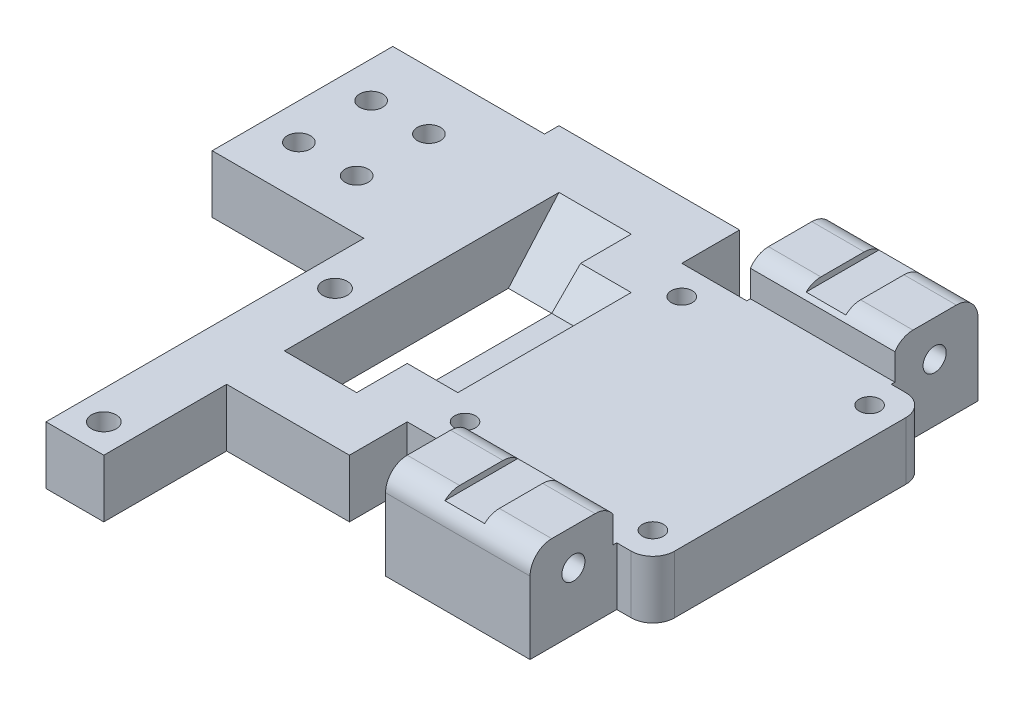
SolidWorks part; units mm, degrees
ref_plane "Front" through (0, 0, 0) normal (0, 0, 1) x (1, 0, 0)
ref_plane "Top" through (0, 0, 0) normal (0, 1, 0) x (1, 0, 0)
ref_plane "Right" through (0, 0, 0) normal (1, 0, 0) x (0, 0, -1)
sketch "Sketch1" plane through (0, 0, 0) normal (0, 1, 0) x (1, 0, 0)
  line L1 (0, 0) -> (300, 0)
  line L2 (0, 0) -> (0, -20)
  line L3 (0, -20) -> (300, -20)
  line L4 (300, 0) -> (300, -20)
  dimension "D1" = 20
  dimension "D2" = 300
extrude "Boss-Extrude1" add sketch "Sketch1" along normal blind 8
sketch "Sketch2" plane through (0, 0, 20) normal (0, 0, 1) x (1, 0, 0)
  line L0 (0, 8) -> (300, 8) construction
  line L1 (0, 0) -> (34, 0)
  line L2 (0, 0) -> (0, 8)
  line L3 (0, 8) -> (34, 8)
  line L4 (34, 0) -> (34, 8)
  line L5 (266, 8) -> (300, 8)
  line L6 (300, 0) -> (300, 8)
  line L7 (266, 0) -> (300, 0)
  line L8 (266, 0) -> (266, 8)
  dimension "D1" = 34
  dimension "D2" = 2
extrude "Boss-Extrude2" add sketch "Sketch2" along normal blind 9
sketch "Sketch3" plane through (0, 0, 0) normal (0, 0, -1) x (-1, 0, 0)
  line L0 (-300, 8) -> (0, 8) construction
  line L1 (0, 0) -> (-34, 0)
  line L2 (0, 0) -> (0, 8)
  line L3 (0, 8) -> (-34, 8)
  line L4 (-34, 0) -> (-34, 8)
  line L5 (-300, 0) -> (-300, 8)
  line L6 (-266, 8) -> (-300, 8)
  line L7 (-266, 0) -> (-266, 8)
  line L8 (-266, 0) -> (-300, 0)
  dimension "D1" = 34
  dimension "D2" = 2
extrude "Boss-Extrude3" add sketch "Sketch3" along normal blind 9
sketch "Sketch4" plane through (0, 8, 0) normal (0, 1, 0) x (1, 0, 0)
  line L0 (0, 9) -> (34, 9) construction
  line L1 (0, 9) -> (0, -29) construction
  circle A0 centre (4, 5) radius 1.45
  circle A1 centre (30, 5) radius 1.45
  circle A2 centre (30, -25) radius 1.45
  circle A3 centre (4, -25) radius 1.45
  circle A4 centre (296, -25) radius 1.45
  circle A5 centre (296, 5) radius 1.45
  circle A6 centre (270, -25) radius 1.45
  circle A7 centre (270, 5) radius 1.45
  dimension "D1" = 2.9
  dimension "D2" = 4
  dimension "D3" = 4
  dimension "D4" = 2
  dimension "D5" = 2
  dimension "D6" = 2
extrude "Cut-Extrude1" cut sketch "Sketch4" against normal through all
sketch "Sketch5" plane through (0, 0, 20) normal (0, 0, 1) x (1, 0, 0)
  line L0 (34, 8) -> (266, 8) construction
  line L1 (266, 0) -> (241, 0)
  line L2 (266, 0) -> (266, 8)
  line L3 (266, 8) -> (241, 8)
  line L4 (241, 0) -> (241, 8)
  dimension "D1" = 25
extrude "Boss-Extrude4" add sketch "Sketch5" along normal blind 17
sketch "Sketch6" plane through (0, 0, 0) normal (0, 0, -1) x (-1, 0, 0)
  line L0 (-266, 0) -> (-34, 0) construction
  line L1 (-266, 8) -> (-241, 8)
  line L2 (-266, 8) -> (-266, 0)
  line L3 (-266, 0) -> (-241, 0)
  line L4 (-241, 8) -> (-241, 0)
  dimension "D1" = 25
extrude "Boss-Extrude5" add sketch "Sketch6" along normal blind 17
sketch "Sketch7" plane through (0, 8, 0) normal (0, 1, 0) x (1, 0, 0)
  line L0 (266, -37) -> (241, -37) construction
  line L1 (259, -29) -> (249, -29)
  line L2 (259, -29) -> (259, 9)
  line L3 (259, 9) -> (249, 9)
  line L4 (249, -29) -> (249, 9)
  line L5 (241, -37) -> (241, -20) construction
  dimension "D1" = 10
  dimension "D2" = 38
  dimension "D3" = 8
  dimension "D4" = 8
extrude "Cut-Extrude2" cut sketch "Sketch7" against normal through all
sketch "Sketch8" plane through (0, 8, 0) normal (0, 1, 0) x (1, 0, 0)
  line L0 (259, -29) -> (259, 9) construction
  line L1 (259, -18) -> (266, -18)
  line L2 (259, -18) -> (259, -2)
  line L3 (259, -2) -> (266, -2)
  line L4 (266, -18) -> (266, -2)
  line L5 (266, -37) -> (241, -37) construction
  dimension "D1" = 7
  dimension "D2" = 16
  dimension "D3" = 19
extrude "Cut-Extrude3" cut sketch "Sketch8" against normal blind 4
sketch "Sketch9" plane through (259, 0, 0) normal (-1, 0, 0) x (0, 0, 1)
  line L0 (18, 4) -> (22, 8)
  line L1 (29, 8) -> (18, 8) construction
  line L2 (22, 8) -> (18, 8)
  line L3 (18, 8) -> (18, 4)
  line L4 (2, 4) -> (-2, 8)
  line L5 (2, 8) -> (-9, 8) construction
  line L6 (-2, 8) -> (2, 8)
  line L7 (2, 8) -> (2, 4)
  dimension "D1" = 4
  dimension "D2" = 4
extrude "Cut-Extrude4" cut sketch "Sketch9" against normal blind 7
sketch "Sketch10" plane through (259, 0, 0) normal (-1, 0, 0) x (0, 0, 1)
  line L0 (-9, 8) -> (-2, 0)
  line L1 (29, 0) -> (-9, 0) construction
  line L2 (-2, 0) -> (-9, 0)
  line L3 (-9, 0) -> (-9, 8)
  line L4 (29, 8) -> (22, 0)
  line L5 (22, 0) -> (29, 0)
  line L6 (29, 0) -> (29, 8)
  line L7 (-51.4523, 12.1971) -> (-51.8778, 12.5861)
  line M6 (-9, 8) -> (-9, 0)
  line M7 (-9, 0) -> (29, 0)
  line M8 (29, 0) -> (29, 8)
  dimension "D1" = 7
  dimension "D2" = 7
extrude "Boss-Extrude6" add sketch "Sketch10" along normal blind 10 contours L0 M6 M7 | L4 M8 M7
sketch "Sketch12" plane through (0, 0, 37) normal (0, 0, 1) x (1, 0, 0)
  line L0 (241, 0) -> (266, 0) construction
  line L1 (241, 8) -> (249, 8)
  line L2 (241, 8) -> (241, 0)
  line L3 (241, 0) -> (249, 0)
  line L4 (249, 8) -> (249, 0)
  dimension "D1" = 8
extrude "Boss-Extrude7" add sketch "Sketch12" along normal blind 17
sketch "Sketch13" plane through (0, 8, 0) normal (0, 1, 0) x (1, 0, 0)
  line L0 (249, -54) -> (241, -54) construction
  line L1 (249, -54) -> (249, -37) construction
  circle A0 centre (245, -50) radius 1.7
  circle A1 centre (245, -18) radius 1.7
  dimension "D1" = 3.4
  dimension "D2" = 4
  dimension "D3" = 4
  dimension "D4" = 2
extrude "Cut-Extrude6" cut sketch "Sketch13" against normal through all
sketch "Sketch14" plane through (0, 0, 29) normal (0, 0, 1) x (1, 0, 0)
  line L1 (295, 13) -> (275, 13)
  line L2 (295, 13) -> (295, 0)
  line L3 (295, 0) -> (275, 0)
  line L4 (275, 13) -> (275, 0)
  line L5 (266, 0) -> (300, 0) construction
  line L7 (266, 8) -> (266, 0) construction
  dimension "D1" = 20
  dimension "D2" = 9
  dimension "D3" = 13
extrude "Boss-Extrude8" add sketch "Sketch14" along normal blind 12
sketch "Sketch15" plane through (295, 0, 0) normal (1, 0, 0) x (0, 0, -1)
  line L0 (-41, 0) -> (-41, 13) construction
  line L1 (-41, 13) -> (-29, 13) construction
  circle A0 centre (-35, 8) radius 1.6
  dimension "D1" = 3.2
  dimension "D2" = 6
  dimension "D3" = 5
extrude "Cut-Extrude7" cut sketch "Sketch15" against normal blind 20
sketch "Sketch16" plane through (0, 0, -9) normal (0, 0, -1) x (-1, 0, 0)
  line L1 (-295, 13) -> (-275, 13)
  line L2 (-295, 13) -> (-295, 0)
  line L3 (-295, 0) -> (-275, 0)
  line L4 (-275, 13) -> (-275, 0)
  line L5 (-300, 0) -> (-266, 0) construction
  line L6 (-266, 0) -> (-266, 8) construction
  dimension "D1" = 20
  dimension "D2" = 9
  dimension "D3" = 13
extrude "Boss-Extrude9" add sketch "Sketch16" along normal blind 12
sketch "Sketch17" plane through (295, 0, 0) normal (1, 0, 0) x (0, 0, -1)
  line L1 (21, 13) -> (21, 0) construction
  line L2 (21, 13) -> (9, 13) construction
  circle A0 centre (15, 8) radius 1.6
  dimension "D1" = 3.2
  dimension "D2" = 5
  dimension "D3" = 6
extrude "Cut-Extrude8" cut sketch "Sketch17" against normal blind 20
sketch "Sketch18" plane through (0, 0, -9) normal (0, 0, -1) x (-1, 0, 0)
  line L1 (-25, 13) -> (-5, 13)
  line L2 (-25, 13) -> (-25, 0)
  line L3 (-25, 0) -> (-5, 0)
  line L4 (-5, 13) -> (-5, 0)
  line L5 (-34, 0) -> (0, 0) construction
  line L6 (-34, 8) -> (-34, 0) construction
  dimension "D1" = 20
  dimension "D2" = 9
  dimension "D3" = 13
extrude "Boss-Extrude10" add sketch "Sketch18" along normal blind 12
sketch "Sketch19" plane through (5, 0, 0) normal (-1, 0, 0) x (0, 0, 1)
  line L0 (-21, 0) -> (-21, 13) construction
  line L1 (-21, 13) -> (-9, 13) construction
  circle A0 centre (-15, 8) radius 1.6
  dimension "D1" = 3.2
  dimension "D2" = 6
  dimension "D3" = 5
extrude "Cut-Extrude9" cut sketch "Sketch19" against normal blind 20
sketch "Sketch20" plane through (0, 0, 29) normal (0, 0, 1) x (1, 0, 0)
  line L1 (5, 13) -> (25, 13)
  line L2 (5, 13) -> (5, 0)
  line L3 (5, 0) -> (25, 0)
  line L4 (25, 13) -> (25, 0)
  line L5 (0, 0) -> (34, 0) construction
  line L6 (34, 0) -> (34, 8) construction
  dimension "D1" = 20
  dimension "D2" = 9
  dimension "D3" = 13
extrude "Boss-Extrude11" add sketch "Sketch20" along normal blind 12
sketch "Sketch21" plane through (5, 0, 0) normal (-1, 0, 0) x (0, 0, 1)
  line L0 (41, 13) -> (41, 0) construction
  line L2 (41, 13) -> (29, 13) construction
  circle A0 centre (35, 8) radius 1.6
  dimension "D1" = 3.2
  dimension "D2" = 6
  dimension "D3" = 5
extrude "Cut-Extrude10" cut sketch "Sketch21" against normal blind 20
fillet "Fillet6" radius 3 8 edges at (15, 13, 41) (15, 13, 29) (15, 13, -9) (15, 13, -21) (285, 13, 41) (285, 13, 29) (285, 13, -9) (285, 13, -21)
sketch "Sketch28" plane through (0, 0, 0) normal (-1, 0, 0) x (0, 0, 1)
  line L1 (78.9453, 217.6934) -> (-119.9362, 217.6934)
  line L2 (78.9453, 217.6934) -> (78.9453, -338.6618)
  line L3 (78.9453, -338.6618) -> (-119.9362, -338.6618)
  line L4 (-119.9362, 217.6934) -> (-119.9362, -338.6618)
extrude "Cut-Extrude14" cut sketch "Sketch28" against normal blind 220
sketch "Sketch29" plane through (0, 0, 0) normal (0, 0, -1) x (-1, 0, 0)
  line L1 (-241, 0) -> (-220, 0)
  line L2 (-241, 0) -> (-241, 8)
  line L3 (-241, 8) -> (-220, 8)
  line L4 (-220, 0) -> (-220, 8)
extrude "Boss-Extrude12" add sketch "Sketch29" along normal blind 15
sketch "Sketch30" plane through (0, 0, 0) normal (0, -1, 0) x (-1, 0, 0)
  line L1 (-220, -20) -> (-241, -20)
  line L2 (-220, -20) -> (-220, -10)
  line L3 (-220, -10) -> (-241, -10)
  line L4 (-241, -20) -> (-241, -10)
  dimension "D1" = 21
  dimension "D2" = 10
extrude "Cut-Extrude15" cut sketch "Sketch30" against normal through all
sketch "Sketch31" plane through (0, 0, 0) normal (0, -1, 0) x (-1, 0, 0)
  line L0 (-220, -10) -> (-220, 15) construction
  line L1 (-241, 15) -> (-220, 15) construction
  line L2 (-220, -10) -> (-241, -10) construction
  circle A0 centre (-225, 7) radius 1.6
  circle A1 centre (-225, -3) radius 1.6
  circle A2 centre (-233, 7) radius 1.6
  circle A3 centre (-233, -3) radius 1.6
  dimension "D1" = 3.2
  dimension "D2" = 3.2
  dimension "D3" = 3.2
  dimension "D4" = 3.2
  dimension "D5" = 5
  dimension "D6" = 8
  dimension "D7" = 5
  dimension "D8" = 7
  dimension "D9" = 8
  dimension "D10" = 8
  dimension "D11" = 7
  dimension "D12" = 8
extrude "Cut-Extrude16" cut sketch "Sketch31" against normal through all
fillet "Fillet7" radius 3 2 edges at (300, 4, -9) (300, 4, 29)
sketch "Sketch32" plane through (0, 13, 0) normal (0, 1, 0) x (1, 0, 0)
  line L0 (295, -38) -> (295, -32) construction
  line L1 (287.75, -42.4531) -> (282.25, -42.4531)
  line L2 (287.75, -42.4531) -> (287.75, 28.0104)
  line L3 (287.75, 28.0104) -> (282.25, 28.0104)
  line L4 (282.25, -42.4531) -> (282.25, 28.0104)
  dimension "D1" = 5.5
  dimension "D2" = 7.25
extrude "Cut-Extrude17" cut sketch "Sketch32" against normal blind 0.8
sketch "Sketch33" plane through (0, 0, 29) normal (0, 0, -1) x (-1, 0, 0)
  line L1 (-275, 8) -> (-295, 8)
  line L2 (-275, 8) -> (-275, 12.9638)
  line L3 (-275, 12.9638) -> (-295, 12.9638)
  line L4 (-295, 8) -> (-295, 12.9638)
  dimension "D1" = 20
extrude "Cut-Extrude18" cut sketch "Sketch33" against normal blind 0.5
sketch "Sketch34" plane through (0, 0, -9) normal (0, 0, 1) x (1, 0, 0)
  line L1 (275, 8) -> (295, 8)
  line L2 (275, 8) -> (275, 19.9424)
  line L3 (275, 19.9424) -> (295, 19.9424)
  line L4 (295, 8) -> (295, 19.9424)
  dimension "D1" = 20
extrude "Cut-Extrude19" cut sketch "Sketch34" against normal blind 0.5
